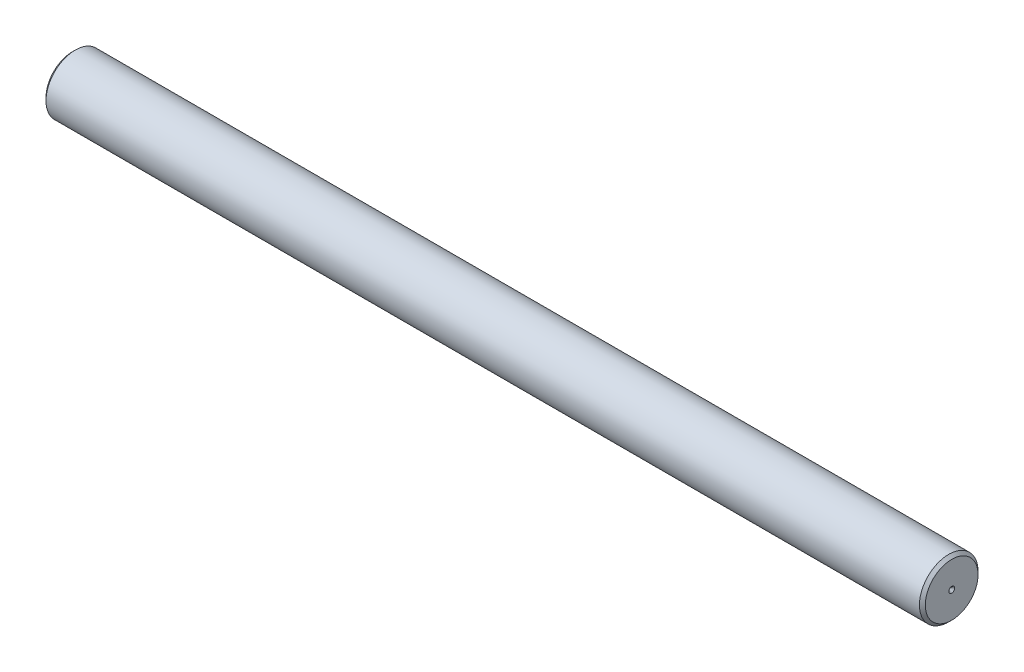
SolidWorks part; units mm, degrees
ref_plane "Front Plane" through (0, 0, 0) normal (0, 0, 1) x (1, 0, 0)
ref_plane "Top Plane" through (0, 0, 0) normal (0, 1, 0) x (1, 0, 0)
ref_plane "Right Plane" through (0, 0, 0) normal (1, 0, 0) x (0, 0, -1)
sketch "Sketch1" plane through (0, 0, 0) normal (0, 0, 1) x (1, 0, 0)
  line L0 (0, 0) -> (150, 0) construction
  line L2 (0, 5) -> (150, 5)
  line L3 (0, 5) -> (0, 0)
  line L4 (0, 0) -> (150, 0)
  line L5 (150, 5) -> (150, 0)
  dimension "L" = 150
  dimension "D_s" = 10
revolve "Revolve1" add sketch "Sketch1" angle 360 about L0
sketch "Sketch2" plane through (0, 0, 0) normal (0, 0, 1) x (1, 0, 0)
  line L0 (0, 0) -> (150, 0) construction
  line L1 (150, -5) -> (150, 5) construction
  line L2 (0, 0.5) -> (0, 0)
  line L3 (0, 0) -> (0.5, 0)
  line L4 (0, 0.5) -> (0.5, 0)
  line L5 (149.5, 0) -> (150, 0.5)
  line L6 (149.5, 0) -> (150, 0)
  line L7 (150, 0.5) -> (150, 0)
  line L8 (0, 5) -> (0, -5) construction
  dimension "D1" = 1
  dimension "D2" = 0.5
revolve "Cut-Revolve1" cut sketch "Sketch2" angle 360 about L0
chamfer "Chamfer1" distance 0.5 angle 45 2 edges at (150, 0, 5) (0, 0, 5)
